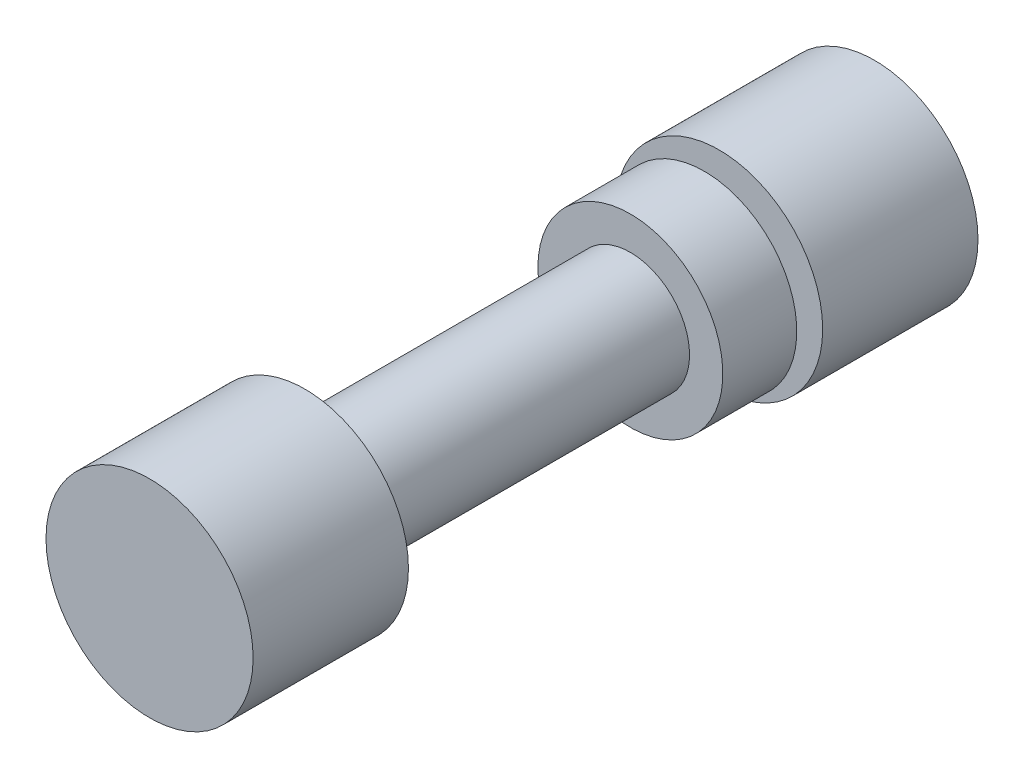
SolidWorks part; units mm, degrees
ref_plane "Plan de face" through (0, 0, 0) normal (0, 0, 1) x (1, 0, 0)
ref_plane "Plan de dessus" through (0, 0, 0) normal (0, 1, 0) x (1, 0, 0)
ref_plane "Plan de droite" through (0, 0, 0) normal (1, 0, 0) x (0, 0, -1)
sketch "Esquisse1" plane through (0, 0, 0) normal (0, 0, 1) x (1, 0, 0)
  circle A2 centre (4, 14.075) radius 1.4
  circle A3 centre (4, 14.075) radius 1.6 construction
  dimension "D1" = 0.2
extrude "Boss.-Extru.1" add sketch "Esquisse1" along normal blind 2.1
sketch "Esquisse2" plane through (0, 0, 2.1) normal (0, 0, 1) x (1, 0, 0)
  circle A0 centre (4, 14.075) radius 0.8
  point P3 (0, 0)
  point P4 (4, 14.075)
  dimension "D1" = 1.6
extrude "Boss.-Extru.2" add sketch "Esquisse2" along normal blind 5.6
sketch "Esquisse3" plane through (0, 0, 7.7) normal (0, 0, 1) x (1, 0, 0)
  circle A1 centre (4, 14.075) radius 1.4 construction
  circle A2 centre (4, 14.075) radius 1.4
extrude "Boss.-Extru.3" add sketch "Esquisse3" along normal blind 2.1
sketch "Esquisse4" plane through (0, 0, 0) normal (0, 0, -1) x (-1, 0, 0)
  circle A0 centre (-4, 14.075) radius 1.25
  dimension "D1" = 2.5
extrude "Boss.-Extru.4" add sketch "Esquisse4" against normal blind 1 from offset 2.3
